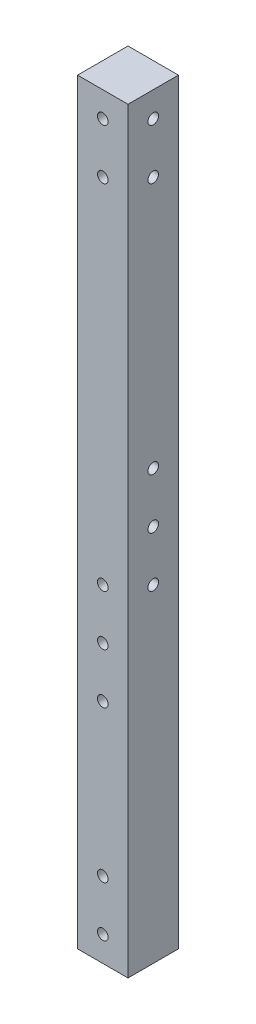
SolidWorks part; units mm, degrees
ref_plane "前视基准面" through (0, 0, 0) normal (0, 0, 1) x (1, 0, 0)
ref_plane "上视基准面" through (0, 0, 0) normal (0, 1, 0) x (1, 0, 0)
ref_plane "右视基准面" through (0, 0, 0) normal (1, 0, 0) x (0, 0, -1)
sketch "草图1" plane through (0, 0, 0) normal (0, 1, 0) x (1, 0, 0)
  line L1 (-10, 10) -> (10, 10)
  line L2 (-10, 10) -> (-10, -10)
  line L3 (-10, -10) -> (10, -10)
  line L4 (10, 10) -> (10, -10)
  line L5 (-10, 10) -> (10, -10) construction
  line L6 (-10, -10) -> (10, 10) construction
  point P0 (0, 0)
  dimension "D1" = 20
  dimension "D2" = 20
extrude "凸台-拉伸1" add sketch "草图1" along normal blind 300
sketch "草图2" plane through (0, 0, 10) normal (0, 0, 1) x (1, 0, 0)
  line L0 (-10, 0) -> (10, 0) construction
  line L1 (-10, 150) -> (10, 150) construction
  line L2 (10, 300) -> (10, 0) construction
  line L3 (-10, 300) -> (-10, 0) construction
  circle A0 centre (0, 10) radius 2.1
  circle A1 centre (0, 30) radius 2.1
  circle A2 centre (0, 270) radius 2.1
  circle A3 centre (0, 290) radius 2.1
  dimension "D1" = 10
  dimension "D3" = 4.2
  dimension "D4" = 4.2
  dimension "D2" = 10
  dimension "D5" = 30
extrude "切除-拉伸1" cut sketch "草图2" against normal through all
sketch "草图3" plane through (10, 0, 0) normal (1, 0, 0) x (0, 0, -1)
  line L3 (10, 300) -> (10, 0) construction
  line L4 (10, 217.21) -> (10, 300)
  line L5 (10, 300) -> (-10, 300)
  line L9 (-10, 300) -> (-10, 228.757)
  line L10 (-10, 300) -> (-10, 0) construction
  line L11 (-10, 228.757) -> (10, 217.21)
  dimension "D1" = 82.79
  dimension "D2" = 120
sketch "草图4" plane through (-10, 0, 0) normal (-1, 0, 0) x (0, 0, 1)
  line L0 (-10, 150) -> (10, 150) construction
  line L1 (-10, 300) -> (-10, 0) construction
  line L2 (10, 300) -> (10, 0) construction
  circle A0 centre (0, 130) radius 2.1
  circle A1 centre (0, 150) radius 2.1
  circle A2 centre (0, 170) radius 2.1
  dimension "D1" = 20
  dimension "D3" = 4.2
  dimension "D2" = 10
  dimension "D5" = 20
  dimension "D4" = 3
extrude "切除-拉伸2" cut sketch "草图4" against normal through all
sketch "草图5" plane through (10, 0, 0) normal (1, 0, 0) x (0, 0, -1)
  line L0 (10, 300) -> (-10, 300) construction
  line L1 (-10, 150) -> (10, 150) construction
  line L2 (-10, 300) -> (-10, 0) construction
  line L3 (10, 300) -> (10, 0) construction
  circle A0 centre (0, 290) radius 2.1
  circle A1 centre (0, 270) radius 2.1
  circle A6 centre (0, 250) radius 2.1 [skipped]
  dimension "D1" = 10
  dimension "D3" = 4.2
  dimension "D2" = 10
  dimension "D5" = 20
  dimension "D4" = 3
extrude "切除-拉伸3" cut sketch "草图5" against normal through all
sketch "草图6" plane through (0, 0, -10) normal (0, 0, -1) x (-1, 0, 0)
  line L0 (10, 300) -> (10, 0) construction
  line L1 (-10, 0) -> (10, 0) construction
  circle A0 centre (0, 90) radius 2.1
  circle A1 centre (0, 110) radius 2.1
  circle A2 centre (0, 130) radius 2.1
  dimension "D1" = 4.2
  dimension "D2" = 10
  dimension "D3" = 90
  dimension "D5" = 20
  dimension "D4" = 3
extrude "切除-拉伸4" cut sketch "草图6" against normal through all
